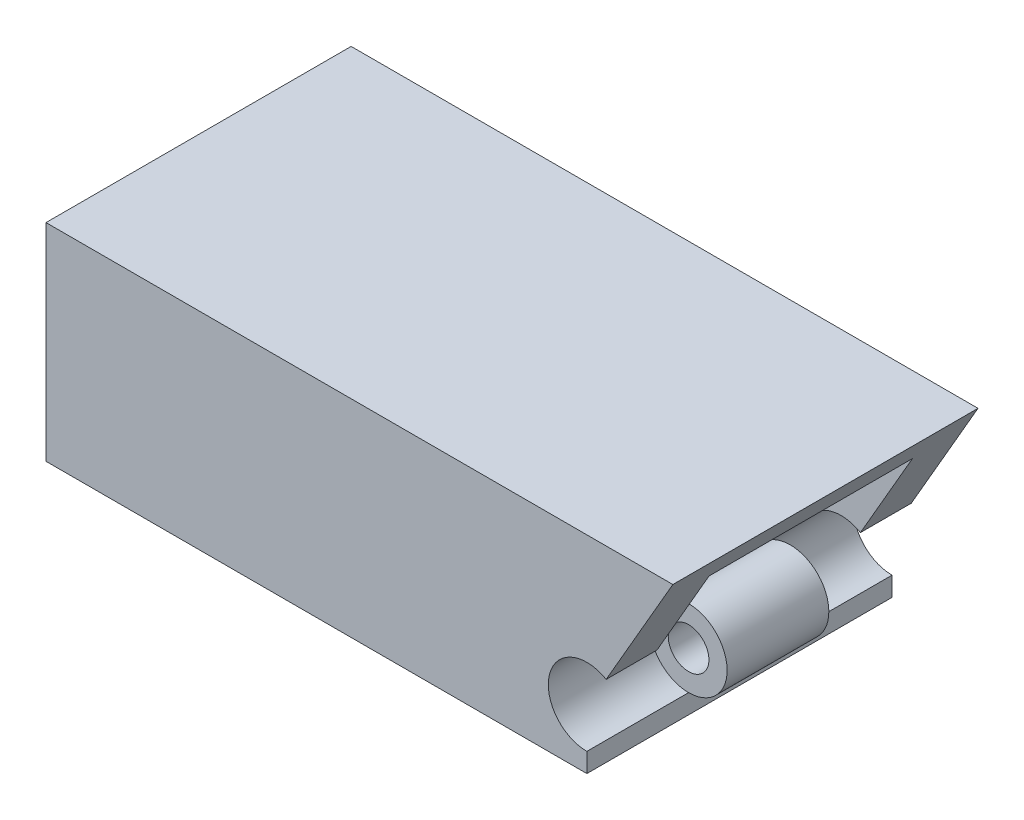
SolidWorks part; units mm, degrees
ref_plane "정면" through (0, 0, 0) normal (0, 0, 1) x (1, 0, 0)
ref_plane "윗면" through (0, 0, 0) normal (0, 1, 0) x (1, 0, 0)
ref_plane "우측면" through (0, 0, 0) normal (1, 0, 0) x (0, 0, -1)
sketch "스케치1" plane through (0, 0, 0) normal (0, 0, 1) x (1, 0, 0)
  line L0 (-7.2879, 10.1647) -> (-13.8475, -1.1969)
  line L1 (-15.7426, -8.2695) -> (-15.7426, -10.1647)
  line L2 (-15.7426, -10.1647) -> (15.8879, -10.1647)
  line L3 (15.8879, -10.1647) -> (15.8879, -8.2695)
  line L4 (13.9928, -1.1969) -> (7.4332, 10.1647)
  line L5 (7.4332, 10.1647) -> (-7.2879, 10.1647)
  line L6 (24.3426, 10.1647) -> (17.783, -1.1969)
  line L7 (24.3426, 10.1647) -> (7.4332, 10.1647)
  line L9 (-7.2879, 10.1647) -> (-37.2879, 10.1647)
  line L10 (-7.2879, 10.1647) -> (-7.2879, -10.1647)
  line L11 (-7.2879, -10.1647) -> (-37.2879, -10.1647)
  line L12 (-37.2879, 10.1647) -> (-37.2879, -10.1647)
  arc A0 (-15.7426, -8.2695) -> (-13.8475, -1.1969) centre (-15.7426, -4.4793) ccw
  arc A1 (15.8879, -8.2695) -> (13.9928, -1.1969) centre (15.8879, -4.4793) ccw
  arc A2 (-15.7426, -8.2695) -> (-13.8475, -1.1969) centre (-15.7426, -4.4793) ccw
  arc A3 (-13.8475, -1.1969) -> (-15.7426, -8.2695) centre (-15.7426, -4.4793) ccw
  circle A4 centre (-15.7426, -4.4793) radius 2
  circle A5 centre (15.8879, -4.4793) radius 2
  point P22 (-7.2879, -10.1647)
  dimension "D1" = 4
  dimension "D2" = 4
  dimension "D3" = 30
extrude "보스-돌출1" add sketch "스케치1" along normal blind 30 contours A3 L0 L9 L12 L11 L1 | A4 | A0 A3 A4 | A0 L1 L2 L10 L0 | A1 L4 L5 L10 L2 L3 A5 | A1 L6 L7 L4
sketch "스케치2" plane through (-37.2879, 0, 0) normal (-1, 0, 0) x (0, 0, 1)
  line L1 (5, 7.6647) -> (25, 7.6647)
  line L2 (5, 7.6647) -> (5, -1.8353)
  line L3 (5, -1.8353) -> (25, -1.8353)
  line L4 (25, 7.6647) -> (25, -1.8353)
  line L5 (30, 10.1647) -> (30, -10.1647) construction
  line L6 (30, 10.1647) -> (0, 10.1647) construction
  dimension "D1" = 20
  dimension "D2" = 9.5
  dimension "D3" = 5
  dimension "D4" = 2.5
extrude "컷-돌출1" cut sketch "스케치2" against normal through all
sketch "스케치3" plane through (0, 0, 30) normal (0, 0, 1) x (1, 0, 0)
  circle A0 centre (15.8879, -4.4793) radius 3.7902
  circle A1 centre (15.8879, -4.4793) radius 2
extrude "보스-돌출2" add sketch "스케치3" against normal blind 30
sketch "스케치4" plane through (0, 0, 30) normal (0, 0, 1) x (1, 0, 0)
  circle A0 centre (15.8879, -4.4793) radius 3.7902
  circle A1 centre (15.8879, -4.4793) radius 2
  arc A2 (15.8879, -8.2695) -> (17.783, -1.1969) centre (15.8879, -4.4793) ccw construction
  circle A3 centre (15.8879, -4.4793) radius 2 construction
extrude "컷-돌출2" cut sketch "스케치4" against normal blind 10 from offset 0
sketch "스케치5" plane through (0, 0, 0) normal (0, 0, -1) x (-1, 0, 0)
  circle A0 centre (-15.8879, -4.4793) radius 3.7902
  circle A1 centre (-15.8879, -4.4793) radius 2
extrude "컷-돌출3" cut sketch "스케치5" against normal blind 10
sketch "스케치6" plane through (-37.2879, 0, 0) normal (-1, 0, 0) x (0, 0, 1)
  line L0 (30, -10.1647) -> (0, -10.1647) construction
  line L1 (5, -1.8353) -> (25, -1.8353)
  line L2 (5, -1.8353) -> (5, -10.1647)
  line L3 (5, -10.1647) -> (25, -10.1647)
  line L4 (25, -1.8353) -> (25, -10.1647)
  point P5 (23.9935, -10.1647)
  point P8 (25, -1.8353)
extrude "컷-돌출4" cut sketch "스케치6" against normal blind 40
